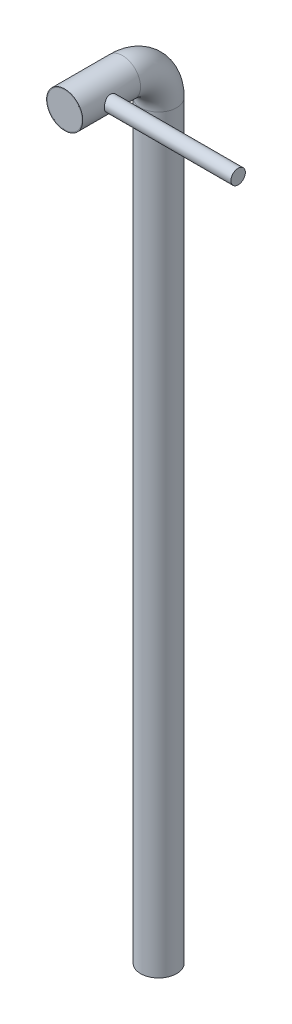
SolidWorks part; units mm, degrees
ref_plane "Ön Düzlem" through (0, 0, 0) normal (0, 0, 1) x (1, 0, 0)
ref_plane "Üst Düzlem" through (0, 0, 0) normal (0, 1, 0) x (1, 0, 0)
ref_plane "Sağ Düzlem" through (0, 0, 0) normal (1, 0, 0) x (0, 0, -1)
sketch "Çizim1" plane through (0, 0, 0) normal (1, 0, 0) x (0, 0, -1)
  line L0 (0, -28.77) -> (0, 75)
  line L1 (-5, 80) -> (-13, 80)
  arc A0 (0, 75) -> (-5, 80) centre (-5, 75) ccw
  point P6 (0, 80)
  dimension "D3" = 5
  dimension "D1" = 108.77
  dimension "D2" = 13
ref_plane "Düzlem1" through (0, 80, 5) normal (0, 0, 1) x (1, 0, 0)
ref_plane "Düzlem2" through (0, 0, 13) normal (0, 0, 1) x (1, 0, 0)
sketch "Çizim2" plane through (0, 0, 13) normal (0, 0, 1) x (1, 0, 0)
  circle A0 centre (0, 80) radius 2.5
  dimension "D1" = 5
sweep "Süpür1" add profiles "Çizim2" path "Çizim1"
shell "İç Boşaltma3" thickness 0.1
ref_plane "Düzlem3" through (20, 0, 0) normal (1, 0, 0) x (0, 0, -1)
sketch "Çizim4" plane through (20, 0, 0) normal (1, 0, 0) x (0, 0, -1)
  line L0 (-13, 82.5) -> (-13, 77.5) construction
  line L1 (-13, 77.5) -> (-5, 77.5) construction
  circle A0 centre (-9, 80) radius 1
  dimension "D1" = 2
  dimension "D2" = 4
  dimension "D3" = 2.5
extrude "Yükseklik-Ekstrüzyon2" add sketch "Çizim4" against normal up to next
surface "Yüzey-Dolgu1"
